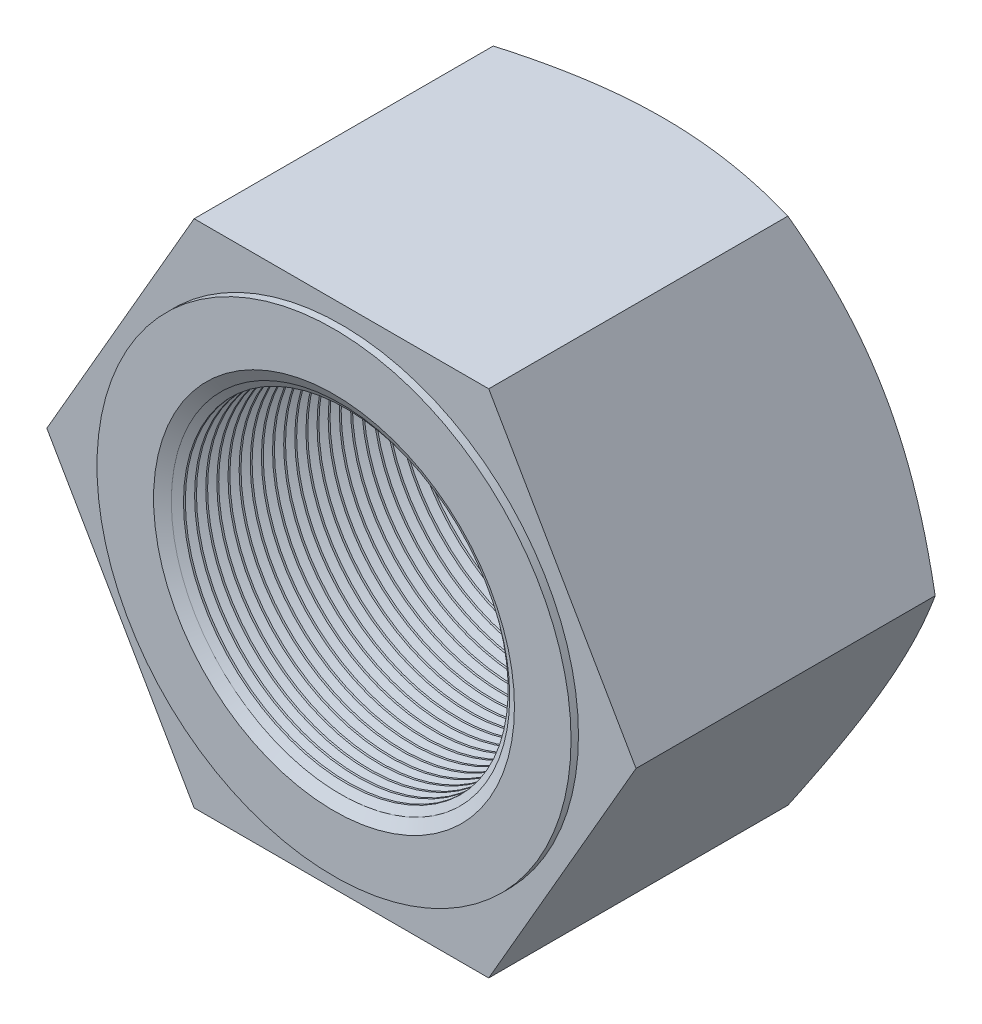
SolidWorks part; units mm, degrees
ref_plane "Front" through (0, 0, 0) normal (0, 0, 1) x (1, 0, 0)
ref_plane "Top" through (0, 0, 0) normal (0, 1, 0) x (1, 0, 0)
ref_plane "Right" through (0, 0, 0) normal (1, 0, 0) x (0, 0, -1)
sketch "Sketch1" plane through (0, 0, 0) normal (0, 0, 1) x (1, 0, 0)
  line L1 (15.8771, -27.5) -> (31.7543, 0)
  line L2 (31.7543, 0) -> (15.8771, 27.5)
  line L3 (15.8771, 27.5) -> (-15.8771, 27.5)
  line L4 (-15.8771, 27.5) -> (-31.7543, 0)
  line L5 (-31.7543, 0) -> (-15.8771, -27.5)
  line L6 (-15.8771, -27.5) -> (15.8771, -27.5)
  circle A0 centre (0, 0) radius 27.5 construction
  circle A1 centre (0, 0) radius 17.5
  dimension "D1" = 35
  dimension "s" = 55
extrude "BaseNut" add sketch "Sketch1" against normal blind 34.7
cosmetic thread "ThreadCosmetic1" [suppressed] parameters "D2"=37
sketch "Sketch2" plane through (-16.7061, 0, -15.0481) normal (0, 1, 0) x (0, 0, 1)
  line L0 (-23.7227, 16.7061) -> (22.0646, 16.7061) construction
  line L2 (-19.6519, 44.2061) -> (-19.6519, 48.4604)
  line L4 (-19.6519, 48.4604) -> (-17.1957, 48.4604)
  line L6 (-17.1957, 48.4604) -> (-19.6519, 44.2061)
  dimension "D1" = 30
  dimension "S1" = 55
revolve "Chamfer1" cut sketch "Sketch2" angle 360 about L0
sketch "Sketch6" plane through (-9.1975, 0, -10.2525) normal (0, 1, 0) x (0, 0, 1)
  line L0 (23.3574, 9.1975) -> (-22.3023, 9.1975) construction
  line L2 (-24.4475, 26.6975) -> (-24.4475, 28.6475)
  line L4 (-24.4475, 28.6475) -> (-23.3216, 26.6975)
  line L6 (-23.3216, 26.6975) -> (-24.4475, 26.6975)
  dimension "da" = 38.9
  dimension "D2" = 60
revolve "EndChamfer1" cut sketch "Sketch6" angle 360 about L0
sketch "Sketch5" plane through (-14.793, 0, -16.9612) normal (0, 1, 0) x (0, 0, 1)
  line L0 (-22.5748, 14.793) -> (24.743, 14.793) construction
  line L2 (16.9612, 40.343) -> (16.9612, 46.5473)
  line L4 (16.9612, 46.5473) -> (13.3792, 46.5473)
  line L6 (13.3792, 46.5473) -> (16.9612, 40.343)
  dimension "dw1" = 51.1
  dimension "D2" = 30
revolve "Chamfer2" [suppressed] cut sketch "Sketch5" angle 360 about L0
sketch "Sketch3" plane through (-18.4892, 11.179, 0) normal (0, 0, 1) x (1, 0, 0)
  circle A1 centre (18.4892, -11.179) radius 17.5 construction
  circle A2 centre (18.4892, -11.179) radius 25.55
  circle A3 centre (18.4892, -11.179) radius 17.5
  dimension "dw" = 51.1
extrude "Extrude1" add sketch "Sketch3" along normal blind 0.8
chamfer "EndChamfer3" distance 1.95 angle 30 1 edges at (17.5, 0, 0.8)
chamfer "EndChamfer2" [suppressed] distance 1.1567 angle 45
sketch "Sketch7" plane through (0, 0, 0) normal (0, 1, 0) x (1, 0, 0)
  line L0 (0, 61.6098) -> (0, -22.305) construction
  line L1 (16.5, 34.0742) -> (17.5, 34.0742)
  line L2 (17.5, 34.0742) -> (18.366, 33.5742)
  line L3 (18.366, 33.5742) -> (17.5, 33.0742)
  line L4 (17.5, 33.0742) -> (16.5, 33.0742)
  line L5 (16.5, 33.0742) -> (16.5, 34.0742)
  line L6 (17.5, 33.5742) -> (-17.5, 33.5742) construction
  dimension "D1" = 1
  dimension "D2" = 35
revolve "Cut-Revolve10" cut sketch "Sketch7" angle 360 about L0
pattern_linear "LPattern10" count 29 spacing 1.2 along (0, 0, 1) of "Cut-Revolve10"
equation "\"D1@EndChamfer3\" = ( \"da@Sketch6\" - \"D1@Sketch1\" )  / 2"
equation "\"D1@EndChamfer2\" = \"m@BaseNut\" / 30"
equation "\"S1@Sketch2\" = \"s@Sketch1\""
equation "\"D2@Sketch7\" = \"D1@Sketch1\""
equation "\"D1@Sketch7\" = (  \"D2@ThreadCosmetic1\" - \"D1@Sketch1\" )  / 2"
equation "\"D3@LPattern10\" = \"D1@Sketch7\" * 1.2"
equation "\"D1@LPattern10\" =  \"m@BaseNut\"  / \"D3@LPattern10\""
